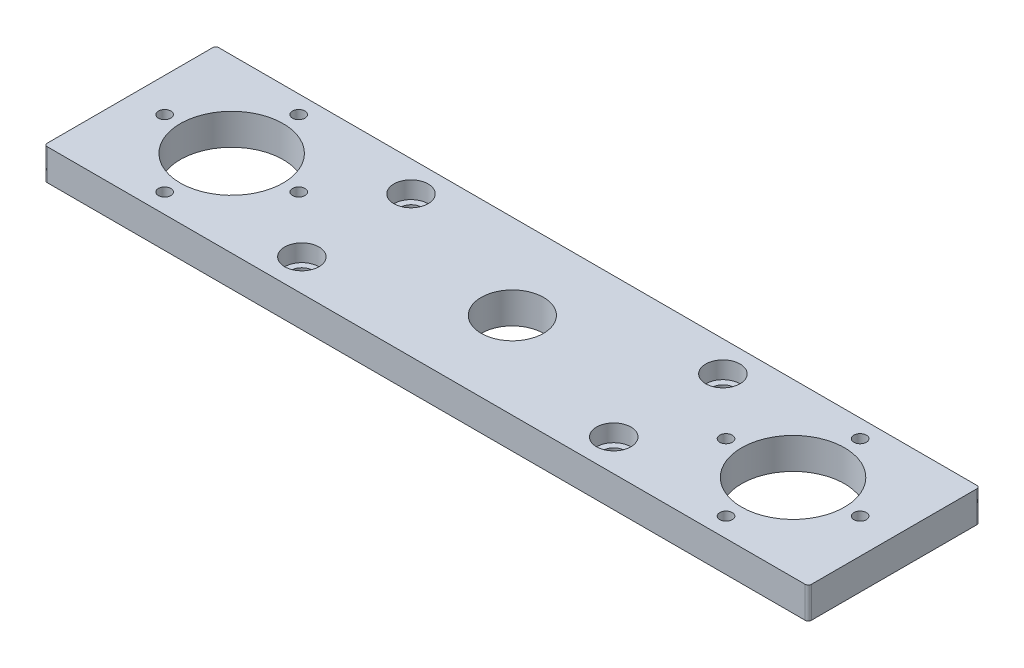
SolidWorks part; units mm, degrees
ref_plane "前视基准面" through (0, 0, 0) normal (0, 0, 1) x (1, 0, 0)
ref_plane "上视基准面" through (0, 0, 0) normal (0, 1, 0) x (1, 0, 0)
ref_plane "右视基准面" through (0, 0, 0) normal (1, 0, 0) x (0, 0, -1)
other "Configuration Table"
sketch "草图1" plane through (0, 0, 0) normal (0, 1, 0) x (1, 0, 0)
  line L1 (0.118, -0.236) -> (245.118, -0.236)
  line L2 (0.118, -0.236) -> (0.118, 54.764)
  line L3 (0.118, 54.764) -> (245.118, 54.764)
  line L4 (245.118, -0.236) -> (245.118, 54.764)
  circle A1 centre (32.5, 27.5) radius 16.5
  circle A3 centre (11, 27.5) radius 2
  circle A4 centre (54, 27.5) radius 2
  circle A5 centre (32.5, 6) radius 2
  circle A6 centre (72.5, 10) radius 3.5
  circle A7 centre (72.5, 45) radius 3.5
  circle A8 centre (32.5, 49) radius 2
  circle A9 centre (212.5, 6) radius 2
  circle A10 centre (172.5, 10) radius 3.5
  circle A11 centre (234, 27.5) radius 2
  circle A12 centre (191, 27.5) radius 2
  circle A13 centre (172.5, 45) radius 3.5
  circle A14 centre (212.5, 49) radius 2
  circle A15 centre (212.5, 27.5) radius 16.5
  circle A17 centre (122.5, 27.5) radius 10
extrude "凸台-拉伸4" add sketch "草图1" along normal blind 10 contours A15 | A17 | A7 | A6 | A13 | A10 | A8 | A4 | A5 | A3 | A14 | A12 | A11 | A9 | A1 | L2 L1 L4 L3
sketch "草图2" plane through (0, 10, 0) normal (0, 1, 0) x (1, 0, 0)
  circle A0 centre (72.5, 45) radius 5.5
  circle A1 centre (72.5, 10) radius 5.5
  circle A2 centre (172.5, 45) radius 5.5
  circle A3 centre (172.5, 10) radius 5.5
extrude "切除-拉伸1" cut sketch "草图2" against normal blind 5.5
fillet "圆角1" radius 1 4 edges at (245.118, 5, 0.236) (245.118, 5, -54.764) (0.118, 5, -54.764) (0.118, 5, 0.236)
